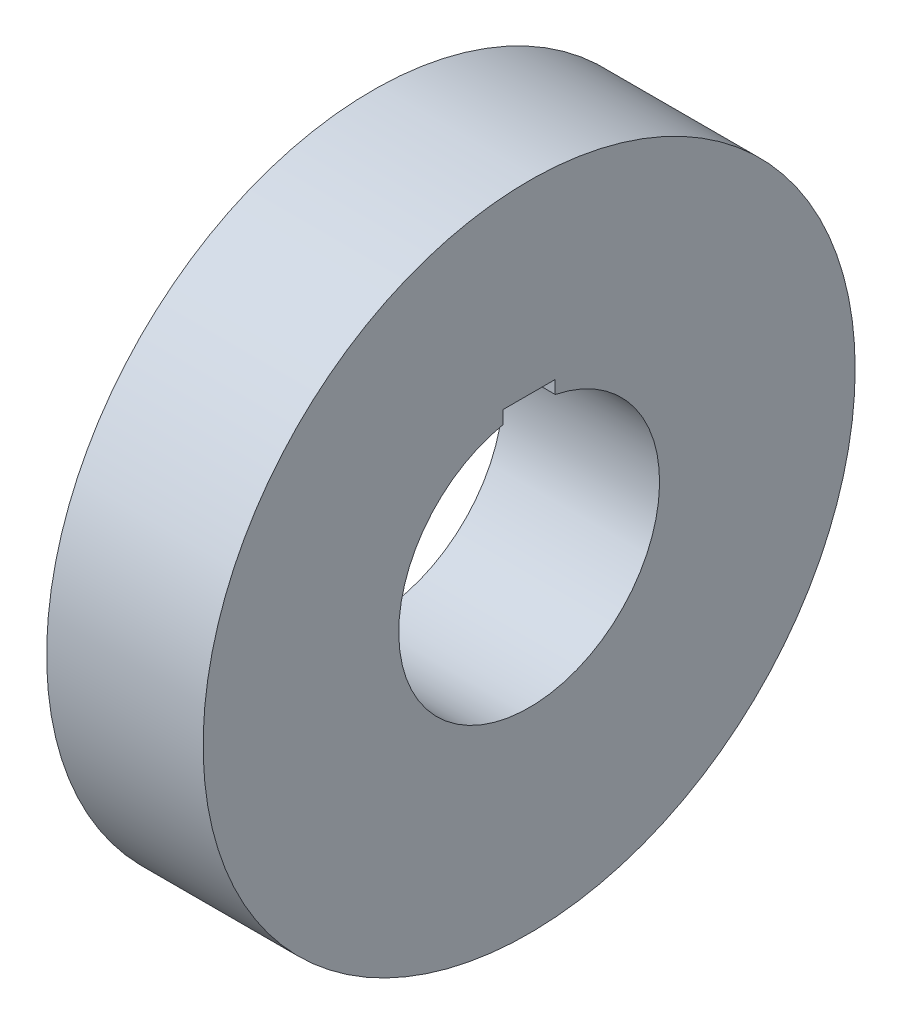
SolidWorks part; units mm, degrees
ref_plane "Front Plane" through (0, 0, 0) normal (0, 0, 1) x (1, 0, 0)
ref_plane "Top Plane" through (0, 0, 0) normal (0, 1, 0) x (1, 0, 0)
ref_plane "Right Plane" through (0, 0, 0) normal (1, 0, 0) x (0, 0, -1)
sketch "Sketch1" plane through (0, 0, 0) normal (1, 0, 0) x (0, 0, -1)
  circle A0 centre (0, 0) radius 25
  circle A1 centre (0, 0) radius 10
  dimension "D1" = 50
  dimension "D2" = 20
extrude "Boss-Extrude1" add sketch "Sketch1" along normal blind 12
sketch "Sketch2" plane through (12, 0, 0) normal (1, 0, 0) x (0, 0, -1)
  line L0 (0, 0) -> (0, 20.3997) construction
  line L1 (2, 10.798) -> (-2, 10.798)
  line L2 (-2, 10.798) -> (-2, 9.798)
  line L3 (2, 10.798) -> (2, 9.798)
  circle A0 centre (0, 0) radius 10 construction
  circle A1 centre (0, 0) radius 10
  point P9 (0, 10.798)
  circle M6 centre (0, 0) radius 10
  dimension "D1" = 4
  dimension "D2" = 1
extrude "Cut-Extrude1" cut sketch "Sketch2" against normal through all contours L0 L1 L2 M6 | L0 A1 L3 L1
equation "\"shaft-diameter\" =20mm"
equation "\"D2@Sketch1\"=\"shaft-diameter\""
